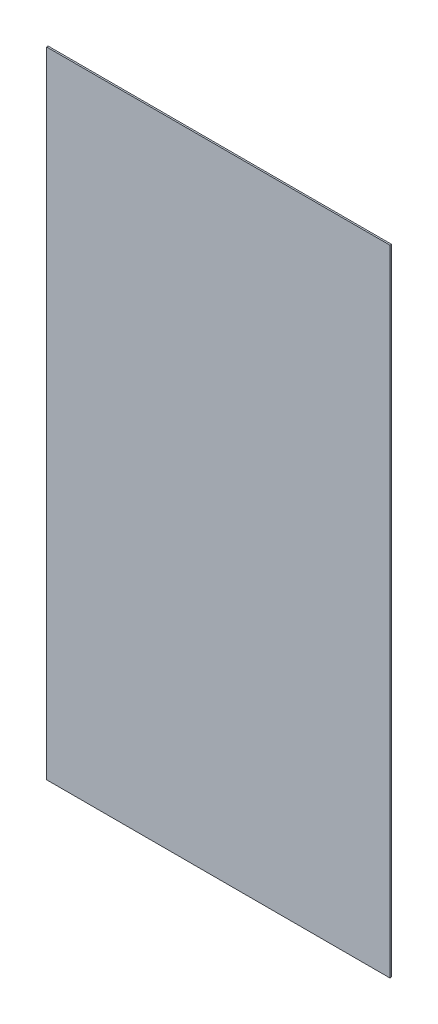
SolidWorks part; units mm, degrees
ref_plane "Front Plane" through (0, 0, 0) normal (0, 0, 1) x (1, 0, 0)
ref_plane "Top Plane" through (0, 0, 0) normal (0, 1, 0) x (1, 0, 0)
ref_plane "Right Plane" through (0, 0, 0) normal (1, 0, 0) x (0, 0, -1)
other "Configuration Table"
sketch "Sketch1" plane through (0, 0, 0) normal (0, 0, 1) x (1, 0, 0)
  line L1 (340, 1340) -> (670, 1340)
  line L2 (340, 1340) -> (340, 1950)
  line L3 (340, 1950) -> (670, 1950)
  line L4 (670, 1340) -> (670, 1950)
extrude "PRESS_panel_ust_sag_1" add sketch "Sketch1" along normal blind 1.5 from offset 38.5 separate body
